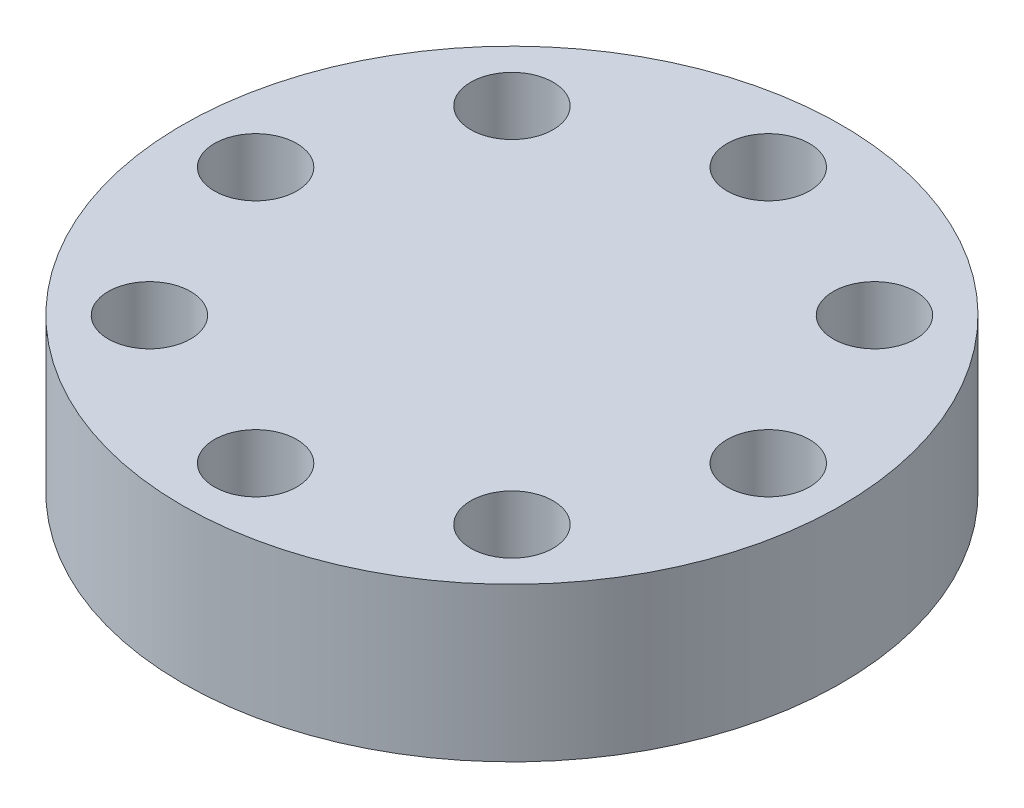
SolidWorks part; units mm, degrees
ref_plane "Front Plane" through (0, 0, 0) normal (0, 0, 1) x (1, 0, 0)
ref_plane "Top Plane" through (0, 0, 0) normal (0, 1, 0) x (1, 0, 0)
ref_plane "Right Plane" through (0, 0, 0) normal (1, 0, 0) x (0, 0, -1)
sketch "Sketch1" plane through (0, 0, 0) normal (0, 1, 0) x (1, 0, 0)
  circle A0 centre (0, 0) radius 9
  dimension "D1" = 18
extrude "BracketMount" add sketch "Sketch1" along normal blind 4.2
sketch "Sketch2" plane through (0, 4.2, 0) normal (0, 1, 0) x (1, 0, 0)
  circle A0 centre (0, 7) radius 1.125
  circle A7 centre (4.9497, 4.9497) radius 1.125
  circle A8 centre (7, 0) radius 1.125
  circle A9 centre (4.9497, -4.9497) radius 1.125
  circle A10 centre (0, -7) radius 1.125
  circle A11 centre (-4.9497, -4.9497) radius 1.125
  circle A12 centre (-7, 0) radius 1.125
  circle A13 centre (-4.9497, 4.9497) radius 1.125
  point P19 (0, 0)
  dimension "D1" = 2.25
  dimension "D3" = 7
extrude "Bracket-MountHoles" cut sketch "Sketch2" against normal up to surface (4.2 mm away) up to face at (0, 0, 9)
sketch "Sketch3" plane through (0, 0, 0) normal (0, -1, 0) x (1, 0, 0)
  circle A0 centre (0, 0) radius 3
  dimension "D1" = 6
extrude "AxleHole" cut sketch "Sketch3" against normal blind 3.7
